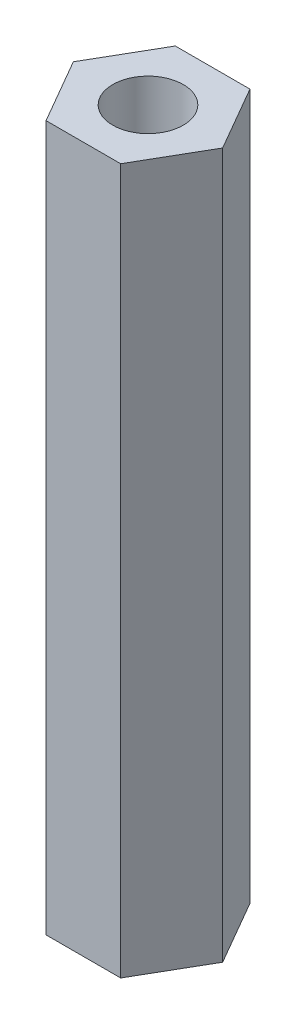
SolidWorks part; units mm, degrees
ref_plane "Front Plane" through (0, 0, 0) normal (0, 0, 1) x (1, 0, 0)
ref_plane "Top Plane" through (0, 0, 0) normal (0, 1, 0) x (1, 0, 0)
ref_plane "Right Plane" through (0, 0, 0) normal (1, 0, 0) x (0, 0, -1)
sketch "Sketch1" plane through (0, 0, 0) normal (0, 1, 0) x (1, 0, 0)
  line L1 (3.1754, 0) -> (1.5877, 2.75)
  line L2 (1.5877, 2.75) -> (-1.5877, 2.75)
  line L3 (-1.5877, 2.75) -> (-3.1754, 0)
  line L4 (-3.1754, 0) -> (-1.5877, -2.75)
  line L5 (-1.5877, -2.75) -> (1.5877, -2.75)
  line L6 (1.5877, -2.75) -> (3.1754, 0)
  circle A0 centre (0, 0) radius 2.75 construction
  dimension "D1" = 5.5
extrude "Boss-Extrude1" add sketch "Sketch1" along normal blind 30
sketch "Sketch2" plane through (0, 30, 0) normal (0, 1, 0) x (1, 0, 0)
  circle A0 centre (0, 0) radius 1.5
  dimension "D1" = 3
extrude "Cut-Extrude1" cut sketch "Sketch2" against normal blind 10
ref_plane "Plane1" through (0, 15, 0) normal (0, -1, 0) x (-1, 0, 0)
mirror "Mirror1" about plane through (0, 15, 0) normal (0, -1, 0) of "Cut-Extrude1"
